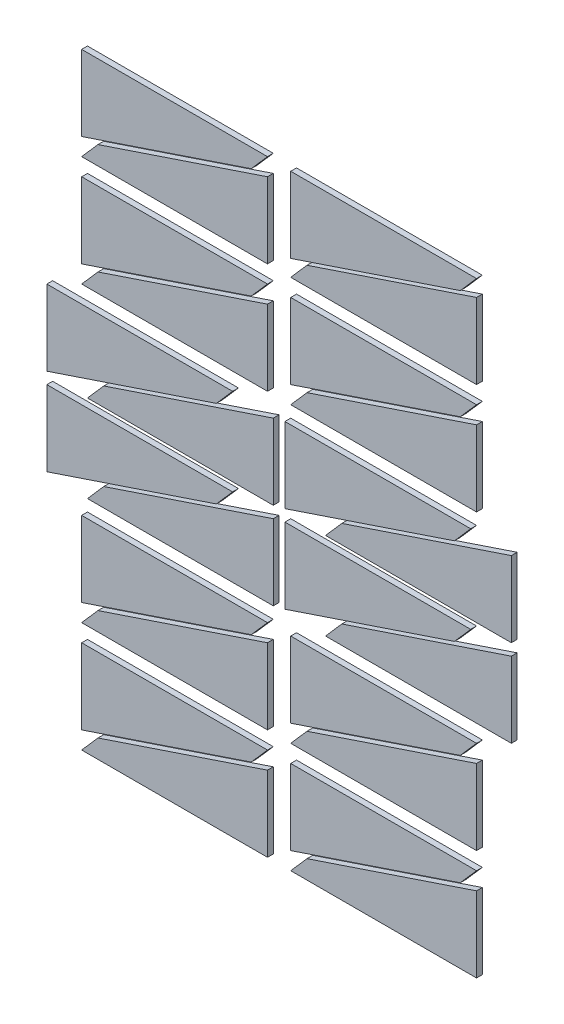
SolidWorks part; units mm, degrees
ref_plane "Front Plane" through (0, 0, 0) normal (0, 0, 1) x (1, 0, 0)
ref_plane "Top Plane" through (0, 0, 0) normal (0, 1, 0) x (1, 0, 0)
ref_plane "Right Plane" through (0, 0, 0) normal (1, 0, 0) x (0, 0, -1)
sketch "20" [suppressed] plane through (0, 0, 0) normal (0, 0, 1) x (1, 0, 0)
  line L0 (6, 0) -> (76, 0) construction
  line L1 (82, 9.5) -> (82, 100) construction
  line L2 (76, 109.5) -> (6, 109.5) construction
  line L3 (0, 100) -> (0, 9.5) construction
  line L4 (6, 0) -> (6, 6.5) construction
  line L5 (3, 9.5) -> (0, 9.5) construction
  line L6 (76, 0) -> (76, 6.5) construction
  line L7 (79, 9.5) -> (82, 9.5) construction
  line L8 (0, 100) -> (3, 100) construction
  line L9 (6, 103) -> (6, 109.5) construction
  line L10 (76, 109.5) -> (76, 103) construction
  line L11 (79, 100) -> (82, 100) construction
  arc A0 (6, 6.5) -> (3, 9.5) centre (3, 6.5) ccw construction
  arc A1 (79, 9.5) -> (76, 6.5) centre (79, 6.5) ccw construction
  arc A2 (3, 100) -> (6, 103) centre (3, 103) ccw construction
  arc A3 (76, 103) -> (79, 100) centre (79, 103) ccw construction
sketch "21" plane through (0, 0, 0) normal (0, 0, 1) x (1, 0, 0)
  line L0 (39, 2.5) -> (7, 2.5)
  line L1 (7, 2.5) -> (9.8, 5.7)
  line L2 (9.8, 5.7) -> (39, 15.5)
  line L3 (39, 15.5) -> (39, 2.5)
  line L4 (7, 18.5) -> (39, 18.5)
  line L5 (39, 18.5) -> (36.2, 15.3)
  line L6 (36.2, 15.3) -> (7, 5.5)
  line L7 (7, 5.5) -> (7, 18.5)
  line L8 (43, 18.5) -> (75, 18.5)
  line L9 (75, 18.5) -> (72.2, 15.3)
  line L10 (72.2, 15.3) -> (43, 5.5)
  line L11 (43, 5.5) -> (43, 18.5)
  line L12 (75, 2.5) -> (43, 2.5)
  line L13 (43, 2.5) -> (45.8, 5.7)
  line L14 (45.8, 5.7) -> (75, 15.5)
  line L15 (75, 15.5) -> (75, 2.5)
  line L16 (39, 21.5) -> (7, 21.5)
  line L17 (7, 21.5) -> (9.8, 24.7)
  line L18 (9.8, 24.7) -> (39, 34.5)
  line L19 (39, 34.5) -> (39, 21.5)
  line L20 (7, 37.5) -> (39, 37.5)
  line L21 (39, 37.5) -> (36.2, 34.3)
  line L22 (36.2, 34.3) -> (7, 24.5)
  line L23 (7, 24.5) -> (7, 37.5)
  line L24 (43, 37.5) -> (75, 37.5)
  line L25 (75, 37.5) -> (72.2, 34.3)
  line L26 (72.2, 34.3) -> (43, 24.5)
  line L27 (43, 24.5) -> (43, 37.5)
  line L28 (75, 21.5) -> (43, 21.5)
  line L29 (43, 21.5) -> (45.8, 24.7)
  line L30 (45.8, 24.7) -> (75, 34.5)
  line L31 (75, 34.5) -> (75, 21.5)
  line L32 (40, 40.5) -> (8, 40.5)
  line L33 (8, 40.5) -> (10.8, 43.7)
  line L34 (10.8, 43.7) -> (40, 53.5)
  line L35 (40, 53.5) -> (40, 40.5)
  line L36 (1, 54) -> (33, 54)
  line L37 (33, 54) -> (30.2, 50.8)
  line L38 (30.2, 50.8) -> (1, 41)
  line L39 (1, 41) -> (1, 54)
  line L40 (42, 54) -> (74, 54)
  line L41 (74, 54) -> (71.2, 50.8)
  line L42 (71.2, 50.8) -> (42, 41)
  line L43 (42, 41) -> (42, 54)
  line L44 (81, 40.5) -> (49, 40.5)
  line L45 (49, 40.5) -> (51.8, 43.7)
  line L46 (51.8, 43.7) -> (81, 53.5)
  line L47 (81, 53.5) -> (81, 40.5)
  line L48 (40, 55.5) -> (8, 55.5)
  line L49 (8, 55.5) -> (10.8, 58.7)
  line L50 (10.8, 58.7) -> (40, 68.5)
  line L51 (40, 68.5) -> (40, 55.5)
  line L52 (1, 69) -> (33, 69)
  line L53 (33, 69) -> (30.2, 65.8)
  line L54 (30.2, 65.8) -> (1, 56)
  line L55 (1, 56) -> (1, 69)
  line L56 (42, 69) -> (74, 69)
  line L57 (74, 69) -> (71.2, 65.8)
  line L58 (71.2, 65.8) -> (42, 56)
  line L59 (42, 56) -> (42, 69)
  line L60 (81, 55.5) -> (49, 55.5)
  line L61 (49, 55.5) -> (51.8, 58.7)
  line L62 (51.8, 58.7) -> (81, 68.5)
  line L63 (81, 68.5) -> (81, 55.5)
  line L64 (39, 72) -> (7, 72)
  line L65 (7, 72) -> (9.8, 75.2)
  line L66 (9.8, 75.2) -> (39, 85)
  line L67 (39, 85) -> (39, 72)
  line L68 (7, 88) -> (39, 88)
  line L69 (39, 88) -> (36.2, 84.8)
  line L70 (36.2, 84.8) -> (7, 75)
  line L71 (7, 75) -> (7, 88)
  line L72 (43, 88) -> (75, 88)
  line L73 (75, 88) -> (72.2, 84.8)
  line L74 (72.2, 84.8) -> (43, 75)
  line L75 (43, 75) -> (43, 88)
  line L76 (75, 72) -> (43, 72)
  line L77 (43, 72) -> (45.8, 75.2)
  line L78 (45.8, 75.2) -> (75, 85)
  line L79 (75, 85) -> (75, 72)
  line L80 (39, 91) -> (7, 91)
  line L81 (7, 91) -> (9.8, 94.2)
  line L82 (9.8, 94.2) -> (39, 104)
  line L83 (39, 104) -> (39, 91)
  line L84 (7, 107) -> (39, 107)
  line L85 (39, 107) -> (36.2, 103.8)
  line L86 (36.2, 103.8) -> (7, 94)
  line L87 (7, 94) -> (7, 107)
  line L88 (43, 106.82) -> (75, 106.82)
  line L89 (75, 106.82) -> (72.2, 103.62)
  line L90 (72.2, 103.62) -> (43, 93.82)
  line L91 (43, 93.82) -> (43, 106.82)
  line L92 (75, 91) -> (43, 91)
  line L93 (43, 91) -> (45.8, 94.2)
  line L94 (45.8, 94.2) -> (75, 104)
  line L95 (75, 104) -> (75, 91)
extrude "Boss-Extrude1" add sketch "21" along normal blind 1
